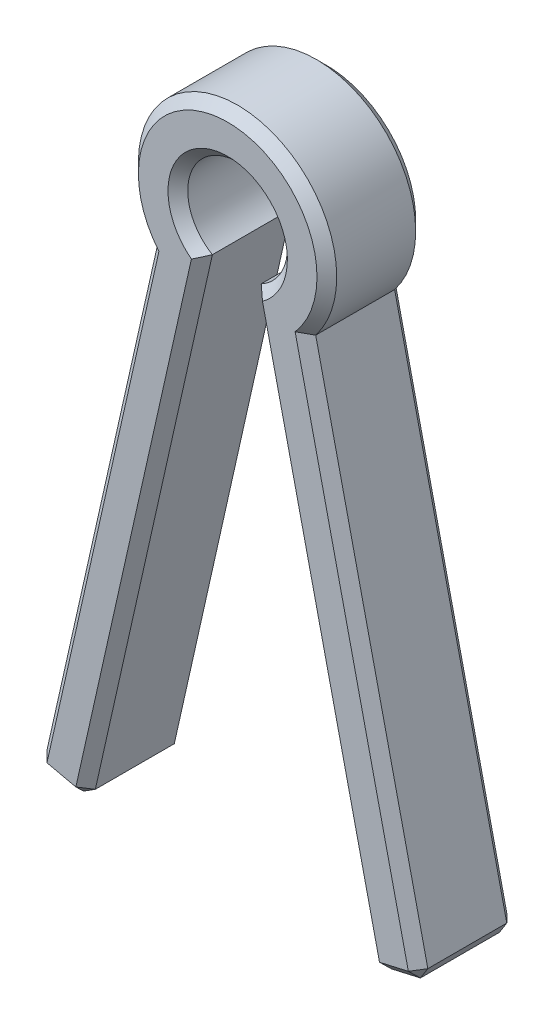
SolidWorks part; units mm, degrees
ref_plane "前视基准面" through (0, 0, 0) normal (0, 0, 1) x (1, 0, 0)
ref_plane "上视基准面" through (0, 0, 0) normal (0, 1, 0) x (1, 0, 0)
ref_plane "右视基准面" through (0, 0, 0) normal (1, 0, 0) x (0, 0, -1)
other "Configuration Table"
sketch "草图1" plane through (0, 0, 0) normal (0, 0, 1) x (1, 0, 0)
  line L0 (0, 0) -> (0, -17.8693) construction
  line L1 (-2.551, -4.3583) -> (-14.6311, -58.1887)
  line L2 (2.3945, -4.4462) -> (14.6311, -58.1887)
  arc A0 (2.3945, -4.4462) -> (-2.551, -4.3583) centre (0, 0) ccw
  point P6 (-2.551, -4.3583)
  point P8 (2.4063, -4.3583)
  point P9 (0, 0)
  point P10 (2.3945, -4.3583)
  dimension "D1" = 10.1
  dimension "D2" = 60
extrude "拉伸-薄壁1" add sketch "草图1" along normal blind 10 thin
chamfer "倒角1" distance 1 angle 45 20 edges at (-17.0705, -57.6413, 0) (-8.5911, -31.2735, 0) (0.0898, 5.0492, 0) (8.5128, -31.3175, 0) (17.0688, -57.6337, 0) (13.7127, -31.6333, 0) (0.1063, 10.0494, 0) (-13.779, -31.5565, 0) (0.1063, 10.0494, 10) (13.7127, -31.6333, 10) (17.0688, -57.6337, 10) (8.5128, -31.3175, 10) (0.0898, 5.0492, 10) (-8.5911, -31.2735, 10) (-17.0705, -57.6413, 10) (-13.779, -31.5565, 10) (19.5064, -57.0787, 5) (14.6311, -58.1887, 5) (-14.6311, -58.1887, 5) (-19.5098, -57.0939, 5)
